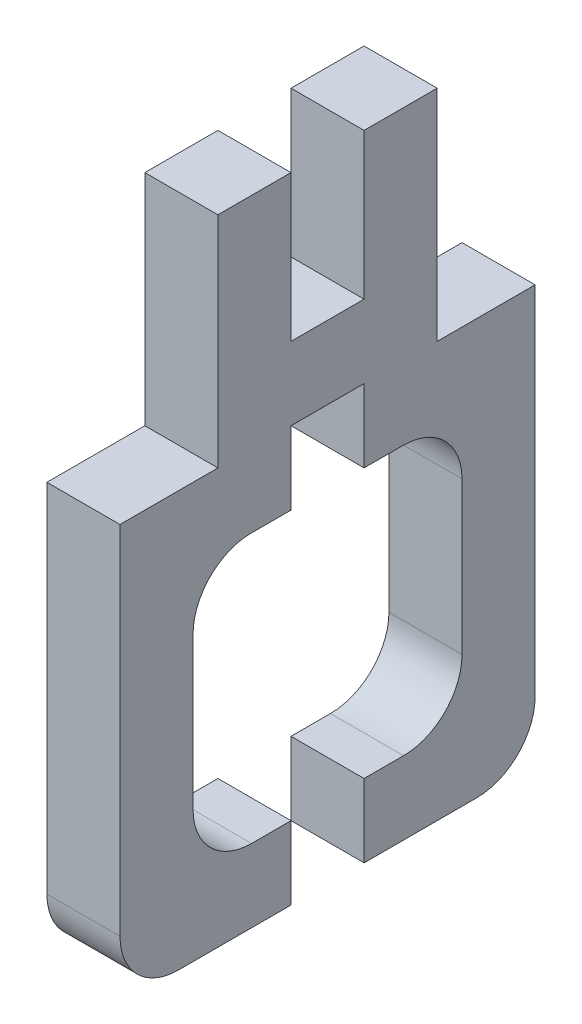
SolidWorks part; units mm, degrees
material "Pine"
ref_plane "Front Plane" through (0, 0, 0) normal (0, 0, 1) x (1, 0, 0)
ref_plane "Top Plane" through (0, 0, 0) normal (0, 1, 0) x (1, 0, 0)
ref_plane "Right Plane" through (0, 0, 0) normal (1, 0, 0) x (0, 0, -1)
sketch "Sketch2" plane through (0, 0, 0) normal (1, 0, 0) x (0, 0, -1)
  line L2 (14.859, 55.118) -> (14.859, 42.418)
  line L3 (14.859, 42.418) -> (21.209, 42.418)
  line L4 (21.209, 42.418) -> (21.209, 55.118)
  line L5 (21.209, 55.118) -> (27.559, 55.118)
  line L7 (30.988, 0) -> (5.08, 0)
  line L9 (11.43, 6.35) -> (24.638, 6.35)
  line L10 (6.35, 11.43) -> (6.35, 24.638)
  line L12 (29.718, 11.43) -> (29.718, 24.638)
  line L16 (27.559, 55.118) -> (27.559, 36.068)
  line L17 (27.559, 36.068) -> (36.068, 36.068)
  line L18 (36.068, 36.068) -> (36.068, 5.08)
  line L20 (8.509, 36.068) -> (0, 36.068)
  line L21 (0, 36.068) -> (0, 5.08)
  line L22 (14.859, 55.118) -> (8.509, 55.118)
  line L23 (8.509, 55.118) -> (8.509, 36.068)
  line L24 (24.638, 29.718) -> (21.209, 29.718)
  line L25 (21.209, 29.718) -> (21.209, 36.068)
  line L26 (21.209, 36.068) -> (14.859, 36.068)
  line L27 (14.859, 36.068) -> (14.859, 29.718)
  line L28 (14.859, 29.718) -> (11.43, 29.718)
  line L30 (14.859, 6.35) -> (21.209, 6.35)
  line L31 (14.859, 6.35) -> (14.859, 0)
  line L32 (14.859, 0) -> (21.209, 0)
  line L33 (21.209, 6.35) -> (21.209, 0)
  arc A0 (11.43, 6.35) -> (6.35, 11.43) centre (11.43, 11.43) cw
  arc A1 (24.638, 6.35) -> (29.718, 11.43) centre (24.638, 11.43) ccw
  arc A2 (24.638, 29.718) -> (29.718, 24.638) centre (24.638, 24.638) cw
  arc A3 (6.35, 24.638) -> (11.43, 29.718) centre (11.43, 24.638) cw
  arc A4 (36.068, 5.08) -> (30.988, 0) centre (30.988, 5.08) cw
  arc A5 (0, 5.08) -> (5.08, 0) centre (5.08, 5.08) ccw
  point P13 (18.034, 42.418)
  point P16 (18.034, 0)
  point P26 (18.034, 0)
  point P30 (6.35, 6.35)
  point P35 (29.718, 29.718)
  point P38 (6.35, 29.718)
  point P43 (0, 0)
  dimension "D15" = 5.08
  dimension "D16" = 5.08
  dimension "D1" = 6.35
  dimension "D2" = 23.368
  dimension "D3" = 23.368
  dimension "D4" = 6.35
  dimension "D5" = 6.35
  dimension "D6" = 6.35
  dimension "D9" = 6.35
  dimension "D10" = 6.35
  dimension "D7" = 6.35
  dimension "D8" = 6.35
  dimension "D11" = 25.4
  dimension "D12" = 6.35
  dimension "D13" = 6.35
  dimension "D14" = 6.35
extrude "Boss-Extrude1" add sketch "Sketch2" along normal blind 6.35 contours L9 L33 L7 L18 L17 L16 L5 L4 L3 L2 L22 L23 L20 L21 L31 L10 L28 L27 L26 L25 L24 L12
equation "\"D2@Sketch2\"=\"D3@Sketch2\""
